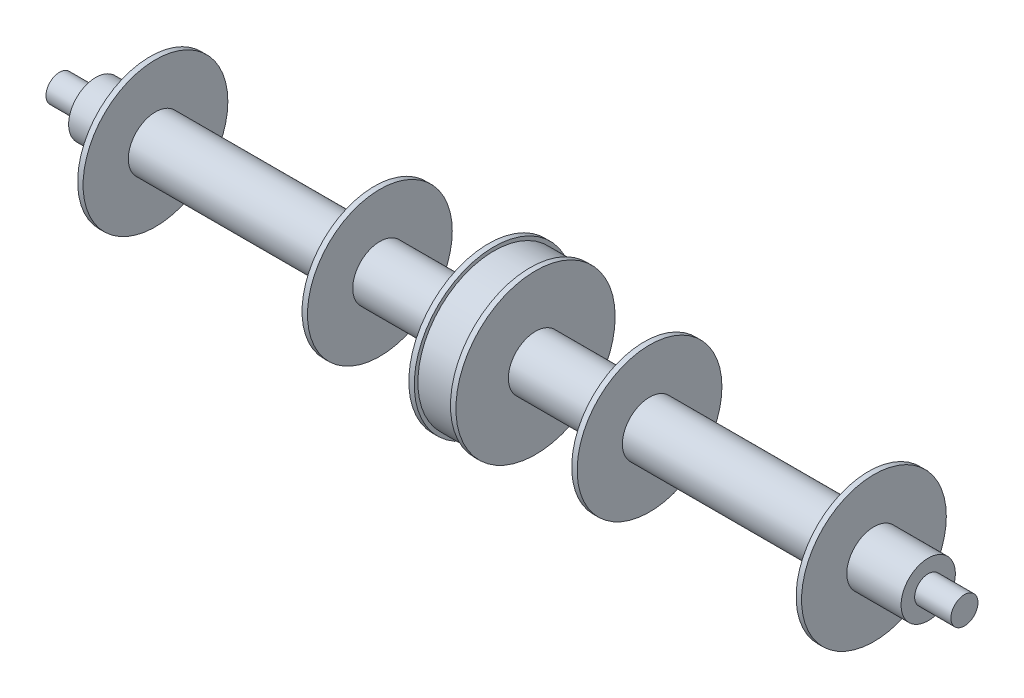
SolidWorks part; units mm, degrees
ref_plane "Front Plane" through (0, 0, 0) normal (0, 0, 1) x (1, 0, 0)
ref_plane "Top Plane" through (0, 0, 0) normal (0, 1, 0) x (1, 0, 0)
ref_plane "Right Plane" through (0, 0, 0) normal (1, 0, 0) x (0, 0, -1)
sketch "Sketch1" plane through (0, 0, 0) normal (0, 0, 1) x (1, 0, 0)
  line L0 (-7.9518, 0) -> (-105.7831, 0) construction
  line L1 (0, 0) -> (0, 69.1566) construction
  line L2 (-125, 0) -> (-125, 3.75)
  line L3 (-125, 3.75) -> (-115, 3.75)
  line L4 (-115, 3.75) -> (-115, 7.5)
  line L5 (-115, 7.5) -> (-100, 7.5)
  line L6 (-100, 7.5) -> (-100, 20)
  line L7 (-100, 20) -> (-98.5, 20)
  line L8 (-98.5, 20) -> (-98.5, 7.5)
  line L9 (-98.5, 7.5) -> (-38, 7.5)
  line L10 (5, 22) -> (5, 21)
  line L11 (6.5, 22) -> (5, 22)
  line L12 (6.5, 7.5) -> (6.5, 22)
  line L13 (36.5, 7.5) -> (6.5, 7.5)
  line L14 (-38, 7.5) -> (-38, 20)
  line L15 (-38, 20) -> (-36.5, 20)
  line L16 (-36.5, 20) -> (-36.5, 7.5)
  line L17 (-36.5, 7.5) -> (-6.5, 7.5)
  line L18 (-6.5, 7.5) -> (-6.5, 22)
  line L19 (-6.5, 22) -> (-5, 22)
  line L20 (-5, 22) -> (-5, 21)
  line L21 (-5, 21) -> (5, 21)
  line L22 (36.5, 20) -> (36.5, 7.5)
  line L23 (38, 20) -> (36.5, 20)
  line L24 (38, 7.5) -> (38, 20)
  line L25 (98.5, 7.5) -> (38, 7.5)
  line L26 (98.5, 20) -> (98.5, 7.5)
  line L27 (100, 20) -> (98.5, 20)
  line L28 (100, 7.5) -> (100, 20)
  line L29 (115, 7.5) -> (100, 7.5)
  line L30 (115, 3.75) -> (115, 7.5)
  line L31 (125, 3.75) -> (115, 3.75)
  line L32 (125, 0) -> (125, 3.75)
  line L33 (-125, 0) -> (125, 0)
  line L34 (-125, 8.842) -> (-125, 5.842) construction
  point P18 (0, 21)
  dimension "D1" = 230
  dimension "D2" = 7.5
  dimension "D3" = 15
  dimension "D4" = 15
  dimension "D5" = 1.5
  dimension "D6" = 2
  dimension "D7" = 10
  dimension "D8" = 1
  dimension "D9" = 40
  dimension "D11" = 30
revolve "Revolve1" add sketch "Sketch1" angle 360 about L0
